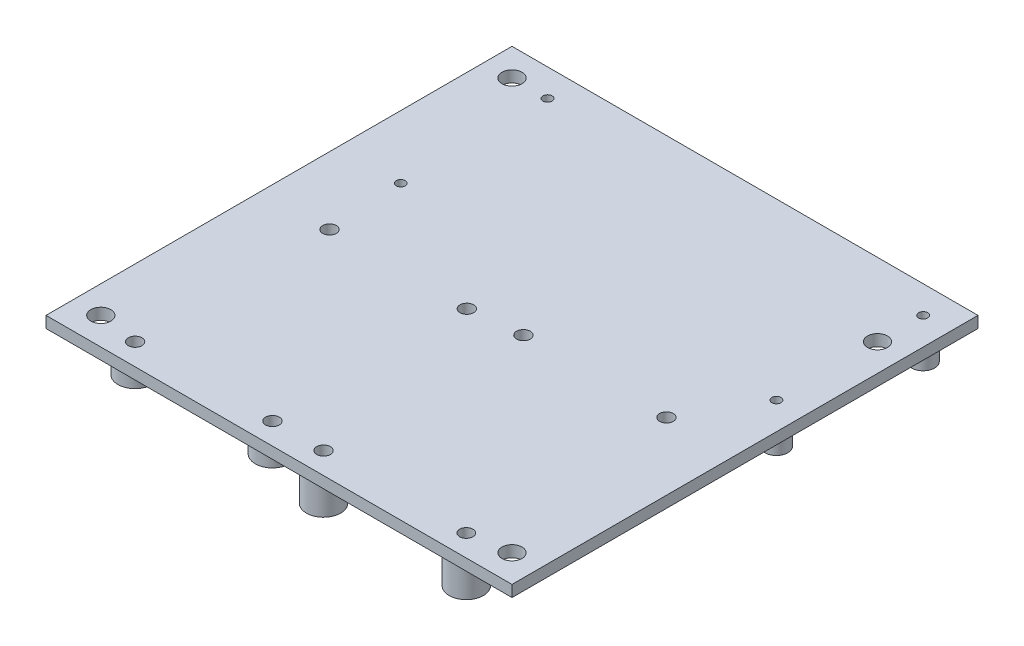
SolidWorks part; units mm, degrees
ref_plane "前基準面" through (0, 0, 0) normal (0, 0, 1) x (1, 0, 0)
ref_plane "上基準面" through (0, 0, 0) normal (0, 1, 0) x (1, 0, 0)
ref_plane "右基準面" through (0, 0, 0) normal (1, 0, 0) x (0, 0, -1)
sketch "草圖1" plane through (0, 0, 0) normal (0, 1, 0) x (1, 0, 0)
  line L1 (-45.7349, 16.1298) -> (36.2651, 16.1298)
  line L2 (-45.7349, 16.1298) -> (-45.7349, -65.8702)
  line L3 (-45.7349, -65.8702) -> (36.2651, -65.8702)
  line L4 (36.2651, 16.1298) -> (36.2651, -65.8702)
  circle A0 centre (-40.7349, 11.1298) radius 1.75
  circle A1 centre (-40.7349, -60.8702) radius 1.75
  circle A2 centre (31.2651, 3.1298) radius 1.75
  circle A3 centre (31.2651, -60.8702) radius 1.75
  dimension "D3" = 3.5
  dimension "D4" = 3.5
  dimension "D5" = 3.5
  dimension "D6" = 3.5
  dimension "D1" = 82
  dimension "D2" = 82
  dimension "D7" = 5
  dimension "D8" = 5
  dimension "D9" = 5
  dimension "D10" = 5
  dimension "D11" = 5
  dimension "D12" = 5
  dimension "D13" = 5
  dimension "D14" = 13
extrude "填料-伸長1" add sketch "草圖1" along normal blind 2
sketch "草圖2" plane through (0, 2, 0) normal (0, 1, 0) x (1, 0, 0)
  line L0 (36.2651, 16.1298) -> (-45.7349, 16.1298) construction
  line L1 (-45.7349, 16.1298) -> (-45.7349, -65.8702) construction
  line L2 (-45.7349, -65.8702) -> (36.2651, -65.8702) construction
  line L3 (36.2651, -65.8702) -> (36.2651, 16.1298) construction
  circle A0 centre (-40.7349, 11.1298) radius 1.75
  circle A1 centre (-34.5149, -14.5702) radius 0.8
  circle A3 centre (31.2651, -14.5702) radius 0.8
  circle A4 centre (-33.7349, -27.8202) radius 1.2
  circle A5 centre (-33.7349, -61.8702) radius 1.2
  circle A6 centre (-9.6849, -27.8202) radius 1.2
  circle A7 centre (-9.6849, -61.8702) radius 1.2
  circle A8 centre (-0.7349, -26.8702) radius 1.2
  circle A9 centre (24.2651, -26.829) radius 1.2
  circle A10 centre (-0.7349, -61.8702) radius 1.2
  circle A11 centre (24.2651, -61.829) radius 1.2
  circle A12 centre (31.2651, 11.1298) radius 0.8
  circle A13 centre (-34.5149, 11.1298) radius 0.8
  dimension "D1" = 3.5
  dimension "D2" = 1.6
  dimension "D3" = 1.6
  dimension "D4" = 1.6
  dimension "D5" = 1.6
  dimension "D6" = 65.78
  dimension "D8" = 5
  dimension "D10" = 2.4
  dimension "D11" = 24.05
  dimension "D12" = 24.05
  dimension "D13" = 25
  dimension "D14" = 25
  dimension "D15" = 34.05
  dimension "D16" = 35
  dimension "D17" = 4
  dimension "D18" = 4
  dimension "D19" = 34.05
  dimension "D20" = 35
  dimension "D21" = 12
  dimension "D22" = 12
  dimension "D25" = 4
  dimension "D26" = 25.7
  dimension "D9" = 5
  dimension "D23" = 12
  dimension "D24" = 12
extrude "除料-伸長1" cut sketch "草圖2" against normal up to next (2 mm away)
sketch "草圖4" plane through (0, 2, 0) normal (0, 1, 0) x (1, 0, 0)
  circle A0 centre (-34.5149, 11.1298) radius 2
  circle A2 centre (-34.5149, 11.1298) radius 0.8
  circle A3 centre (-34.5149, -14.5702) radius 2
  circle A4 centre (-34.5149, -14.5702) radius 0.8
  circle A5 centre (31.2651, 11.1298) radius 2
  circle A6 centre (31.2651, 11.1298) radius 0.8
  circle A7 centre (31.2651, -14.5702) radius 2
  circle A8 centre (31.2651, -14.5702) radius 0.8
  dimension "D1" = 4
extrude "填料-伸長2" add sketch "草圖4" against normal blind 7
sketch "草圖5" plane through (0, 2, 0) normal (0, 1, 0) x (1, 0, 0)
  circle A0 centre (-33.7349, -27.8202) radius 3
  circle A1 centre (-33.7349, -27.8202) radius 1.2
  circle A2 centre (-9.6849, -27.8202) radius 3
  circle A3 centre (-9.6849, -27.8202) radius 1.2
  circle A4 centre (-33.7349, -61.8702) radius 3
  circle A5 centre (-33.7349, -61.8702) radius 1.2
  circle A6 centre (-9.6849, -61.8702) radius 3
  circle A7 centre (-9.6849, -61.8702) radius 1.2
  dimension "D1" = 6
extrude "填料-伸長3" add sketch "草圖5" against normal blind 5
sketch "草圖6" plane through (0, 2, 0) normal (0, 1, 0) x (1, 0, 0)
  circle A0 centre (-0.7349, -26.8702) radius 3
  circle A1 centre (-0.7349, -26.8702) radius 1.2
  circle A2 centre (24.2651, -26.829) radius 3
  circle A3 centre (24.2651, -26.829) radius 1.2
  circle A4 centre (-0.7349, -61.8702) radius 3
  circle A5 centre (-0.7349, -61.8702) radius 1.2
  circle A6 centre (24.2651, -61.8702) radius 3
  circle A7 centre (24.2651, -61.8702) radius 1.1588
  dimension "D1" = 6
extrude "填料-伸長4" add sketch "草圖6" against normal blind 8
sketch "草圖7" plane through (0, 2, 0) normal (0, 1, 0) x (1, 0, 0)
  line L5 (-45.7349, 16.1298) -> (36.2651, 16.1298)
  line L6 (-45.7349, 16.1298) -> (-45.7349, -65.8702)
  line L7 (-45.7349, -65.8702) -> (36.2651, -65.8702)
  line L8 (-45.5349, 15.9298) -> (-45.5349, -65.6702)
  line L9 (-45.5349, -65.6702) -> (36.0651, -65.6702)
  line L10 (36.0651, -65.6702) -> (36.0651, 15.9298)
  line L11 (36.0651, 15.9298) -> (-45.5349, 15.9298)
  line L12 (-45.5349, 15.9298) -> (-45.5349, -65.6702)
  line L13 (-45.5349, -65.6702) -> (36.0651, -65.6702)
  line L14 (36.0651, -65.6702) -> (36.0651, 15.9298)
  line L15 (36.0651, 15.9298) -> (-45.5349, 15.9298)
  line L16 (36.2651, 16.1298) -> (36.2651, -65.8702)
  dimension "D1" = 0.2
extrude "除料-伸長2" cut sketch "草圖7" against normal up to next
